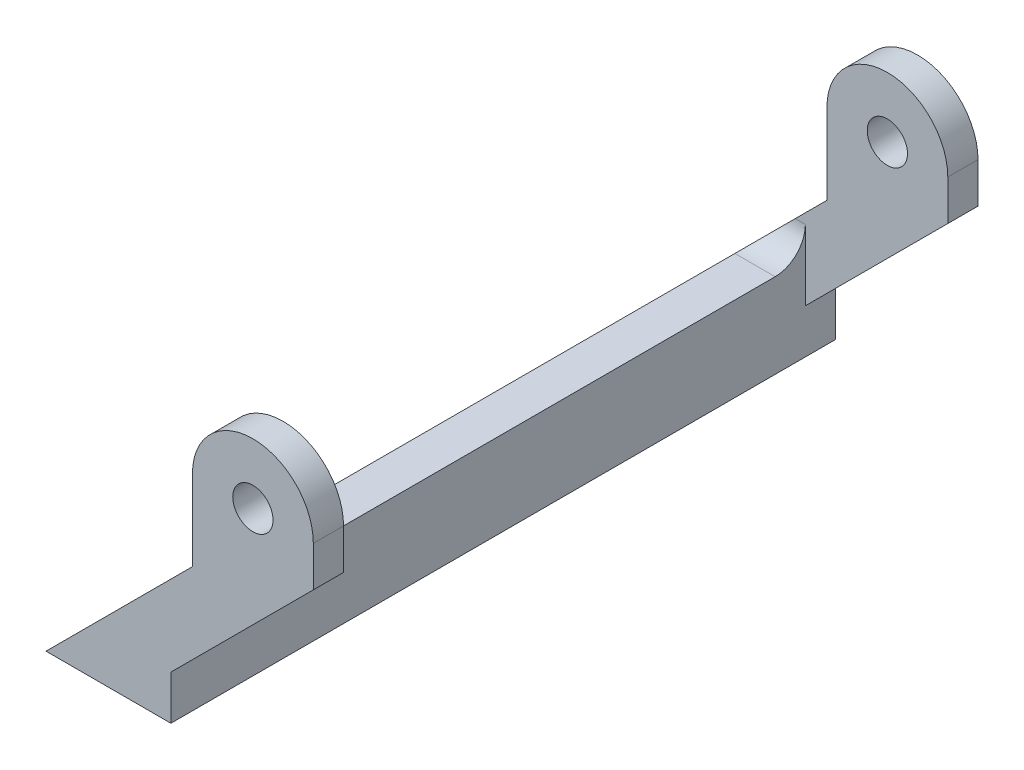
SolidWorks part; units mm, degrees
ref_plane "Front Plane" through (0, 0, 0) normal (0, 0, 1) x (1, 0, 0)
ref_plane "Top Plane" through (0, 0, 0) normal (0, 1, 0) x (1, 0, 0)
ref_plane "Right Plane" through (0, 0, 0) normal (1, 0, 0) x (0, 0, -1)
sketch "Sketch1" plane through (0, 0, 0) normal (0, 0, 1) x (1, 0, 0)
  line L0 (-8.8054, -5.2013) -> (-2.6633, 0.9408)
  line L1 (-4.8054, -5.2013) -> (-8.8054, -5.2013)
  line L2 (-2.6633, 0.9408) -> (-2.6633, 8.9408)
  line L5 (9.3367, 4.9408) -> (9.3367, 8.9408)
  line L6 (-4.8054, -5.2013) -> (-4.8054, -9.2013)
  line L7 (9.3367, 4.9408) -> (-4.8054, -9.2013)
  arc A0 (-2.6633, 8.9408) -> (9.3367, 8.9408) centre (3.3367, 8.9408) cw
  dimension "D4" = 18.1421
  dimension "D1" = 8
  dimension "D6" = 8.1421
  dimension "D5" = 6
  dimension "D2" = 20
  dimension "D3" = 45
  dimension "D7" = 4
  dimension "D8" = 4
extrude "Extrude1" add sketch "Sketch1" along normal blind 3
sketch "Sketch3" plane through (0, 0, 0) normal (0, 0, 1) x (1, 0, 0)
  line L0 (-8.8054, -5.2013) -> (-4.8054, -5.2013)
  line L1 (-4.8054, -5.2013) -> (-4.8054, -13.6013)
  line L2 (-4.8054, -13.6013) -> (-17.2054, -13.6013)
  line L3 (-17.2054, -13.6013) -> (-8.8054, -5.2013)
  dimension "D1" = 45
  dimension "D2" = 4.4
extrude "Extrude2" add sketch "Sketch3" along normal blind 66
sketch "Sketch4" plane through (0, 0, 66) normal (0, 0, 1) x (1, 0, 0)
  line L0 (-8.8054, -5.2013) -> (-4.8054, -5.2013)
  line L1 (-4.8054, -5.2013) -> (-4.8054, -9.2013)
  line L2 (-4.8054, -9.2013) -> (9.3367, 4.9408)
  line L3 (9.3367, 4.9408) -> (9.3367, 8.9408)
  line L4 (-8.8054, -5.2013) -> (-2.6633, 0.9408)
  line L5 (-2.6633, 0.9408) -> (-2.6633, 8.9408)
  line L6 (-4.8054, -13.6013) -> (-4.8054, -5.2013) construction
  line L7 (-17.2054, -13.6013) -> (-4.8054, -13.6013) construction
  arc A0 (-2.6633, 8.9408) -> (9.3367, 8.9408) centre (3.3367, 8.9408) cw
  dimension "D1" = 4.4
extrude "Extrude3" add sketch "Sketch4" against normal blind 3
sketch "Sketch2" plane through (0, 0, 3) normal (0, 0, 1) x (1, 0, 0)
  circle A0 centre (3.3367, 8.9408) radius 2
extrude "Extrude4" cut sketch "Sketch2" against normal up to surface (3 mm away) up to face at (-1.9242, -0.9487, 0)
sketch "Sketch6" plane through (0, 0, 63) normal (0, 0, -1) x (-1, 0, 0)
  circle A0 centre (-3.3367, 8.9408) radius 2
  dimension "D1" = 4
extrude "Extrude5" cut sketch "Sketch6" against normal up to surface (3 mm away) up to face at (-1.9242, -0.9487, 66)
fillet "Fillet3" radius 3 2 edges at (-6.8054, -5.2013, 63) (-6.8054, -5.2013, 3)
